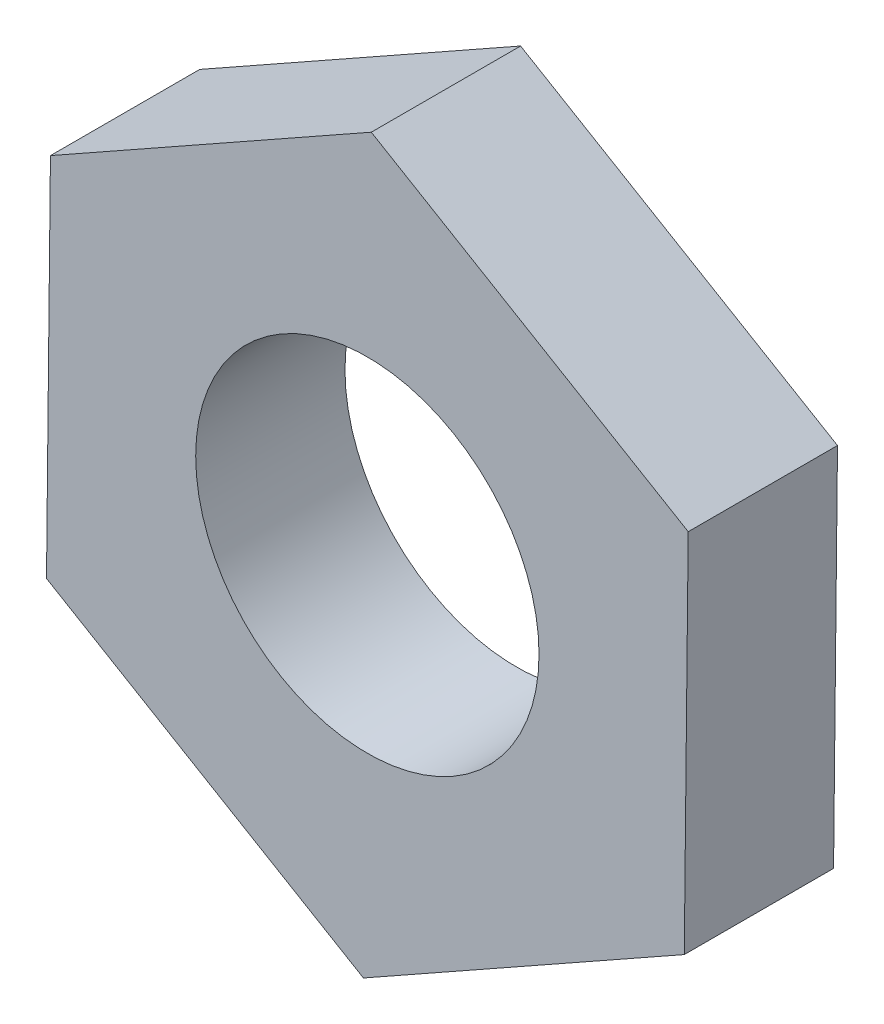
SolidWorks part; units mm, degrees
ref_plane "前视基准面" through (0, 0, 0) normal (0, 0, 1) x (1, 0, 0)
ref_plane "上视基准面" through (0, 0, 0) normal (0, 1, 0) x (1, 0, 0)
ref_plane "右视基准面" through (0, 0, 0) normal (1, 0, 0) x (0, 0, -1)
sketch "草图1" plane through (0, 0, 0) normal (0, 0, 1) x (1, 0, 0)
  line L1 (6.3686, -3.7684) -> (6.4478, 3.6312)
  line L2 (6.4478, 3.6312) -> (0.0792, 7.3996)
  line L3 (0.0792, 7.3996) -> (-6.3686, 3.7684)
  line L4 (-6.3686, 3.7684) -> (-6.4478, -3.6312)
  line L5 (-6.4478, -3.6312) -> (-0.0792, -7.3996)
  line L6 (-0.0792, -7.3996) -> (6.3686, -3.7684)
  circle A0 centre (0, 0) radius 6.4086 construction
  circle A1 centre (0, 0) radius 3.45
  dimension "D2" = 6.9
  dimension "D1" = 14.8
extrude "凸台-拉伸1" add sketch "草图1" along normal blind 3
